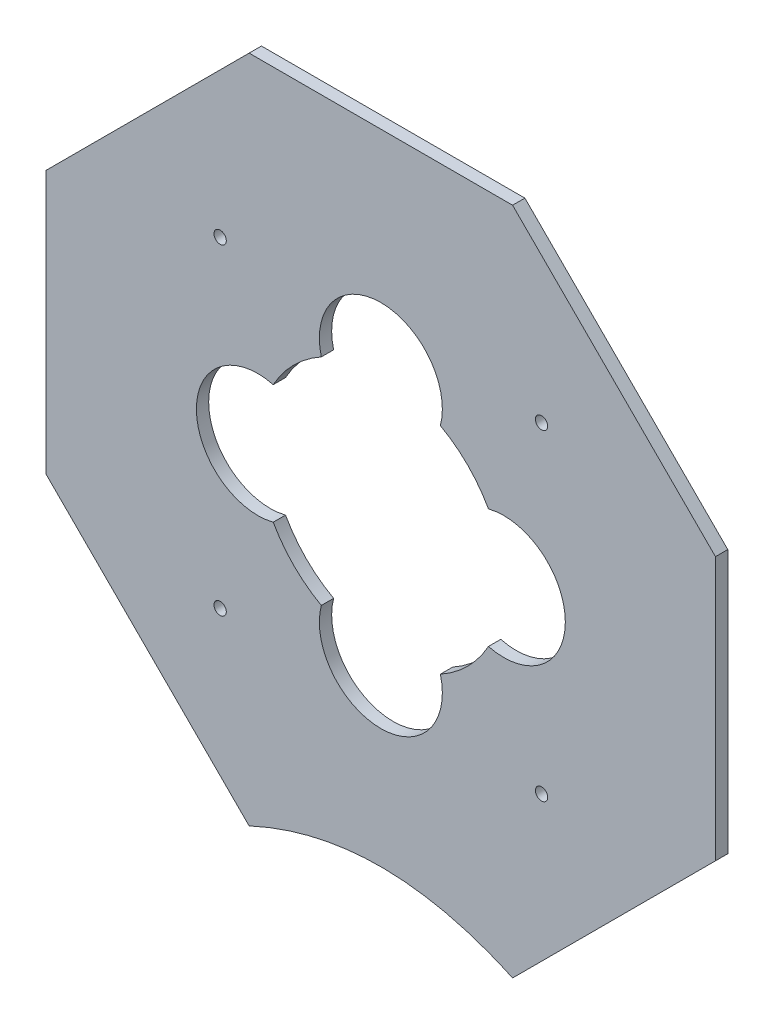
SolidWorks part; units mm, degrees
ref_plane "Front Plane" through (0, 0, 0) normal (0, 0, 1) x (1, 0, 0)
ref_plane "Top Plane" through (0, 0, 0) normal (0, 1, 0) x (1, 0, 0)
ref_plane "Right Plane" through (0, 0, 0) normal (1, 0, 0) x (0, 0, -1)
sketch "Sketch1" plane through (0, 0, 0) normal (0, 0, 1) x (1, 0, 0)
  line L0 (-32.1335, 81.6309) -> (32.1335, 81.6309)
  line L1 (32.1335, 81.6309) -> (81.6309, 32.1335)
  line L2 (81.6309, 32.1335) -> (81.6309, -32.1335)
  line L3 (81.6309, -32.1335) -> (32.1335, -81.6309)
  line L5 (-81.6309, -32.1335) -> (-81.6309, 32.1335)
  line L6 (-81.6309, 32.1335) -> (-32.1335, 81.6309)
  line L7 (-81.6309, -32.1335) -> (-32.1335, -81.6309)
  spline S0 degree 3 poles (-32.1335, -81.6309) (-26.3156, -78.9295) (-17.4585, -75.9069) (-6.4598, -74.367) (0.5039, -74.0955) (13.3814, -74.7374) (24.1945, -77.9193) (32.1335, -81.6309) knots 0 0 0 0 0.289772 0.418867 0.500126 0.604149 1 1 1 1
extrude "Boss-Extrude1" add sketch "Sketch1" along normal blind 3
sketch "Sketch2" plane through (0, 0, 3) normal (0, 0, 1) x (1, 0, 0)
  circle A0 centre (-39.2045, -39.2045) radius 1.5
  circle A1 centre (39.2045, -39.2045) radius 1.5
  circle A2 centre (39.2045, 39.2045) radius 1.5
  circle A3 centre (-39.2045, 39.2045) radius 1.5
extrude "Cut-Extrude1" cut sketch "Sketch2" against normal blind 3 contours A3 | A2 | A1 | A0
sketch "Sketch3" plane through (0, 0, 3) normal (0, 0, 1) x (1, 0, 0)
  circle A0 centre (0, 0) radius 30
  circle A1 centre (-30, 0) radius 15
  circle A2 centre (0, 30) radius 15
  circle A3 centre (30, 0) radius 15
  circle A4 centre (0, -30) radius 15
extrude "Cut-Extrude2" cut sketch "Sketch3" against normal blind 3 contours A0 A2 | A0 A2 | A4 A0 A3 A2 A1 | A0 A1 | A0 A4 | A0 A3 | A0 A3 | A0 A4 | A0 A1
